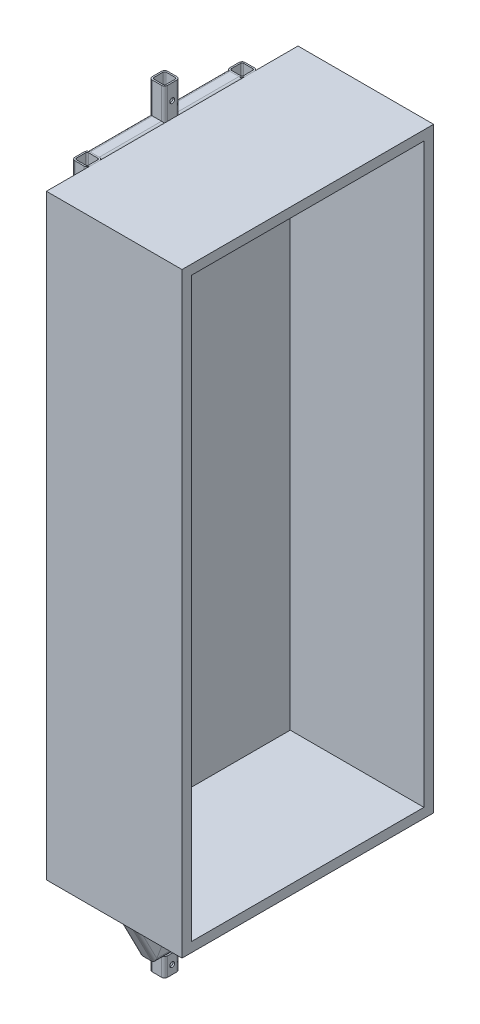
SolidWorks part; units mm, degrees
ref_plane "Front Plane" through (0, 0, 0) normal (1, 0, 0) x (0, 1, 0)
ref_plane "Top Plane" through (0, 0, 0) normal (0, 0, 1) x (0, 1, 0)
ref_plane "Right Plane" through (0, 0, 0) normal (0, 1, 0) x (-1, 0, 0)
sketch "Sketch1" plane through (0, 0, 0) normal (1, 0, 0) x (0, 1, 0)
  line L0 (-254, 254) -> (-254, -254) construction
  line L1 (-482.6, 254) -> (482.6, 254) construction
  line L2 (-482.6, 254) -> (-482.6, -254) construction
  line L3 (-482.6, -254) -> (482.6, -254) construction
  line L4 (482.6, 254) -> (482.6, -254) construction
  line L5 (-482.6, 254) -> (482.6, -254) construction
  line L6 (-482.6, -254) -> (482.6, 254) construction
  line L11 (-254, 133.6842) -> (254, -133.6842) construction
  line L13 (254, 254) -> (254, -254) construction
  point P0 (0, 0)
  point P6 (0, 0)
  dimension "D1" = 965.2
  dimension "D2" = 508
  dimension "D3" = 254
  dimension "D4" = 508
sketch3d "3DSketch1"
  line L0 (0, -381, 101.6) -> (0, -546.5837, 16.5565)
  line L7 (0, 0, 101.6) -> (0, 0, -101.6)
  line L8 (0, -381, 101.6) -> (0, 381, 101.6)
  line L9 (0, 381, 0) -> (0, 431.8, 0)
  line L11 (0, -381, 101.6) -> (0, -381, -101.6)
  line L12 (0, -381, -101.6) -> (0, 381, -101.6)
  line L13 (0, 381, 101.6) -> (0, 381, -101.6)
  line L14 (0, -381, 101.6) -> (0, 381, -101.6) construction
  line L15 (0, -381, -101.6) -> (0, 381, 101.6) construction
  line L16 (0, 254, 127) -> (0, 254, -127)
  line L17 (0, 254, 254) -> (0, 254, -254) construction
  line L18 (0, -546.5837, -16.4635) -> (0, -381, -101.6)
  line L19 (0, -546.5837, 16.5565) -> (0, -546.5837, -16.4635)
  line L20 (0, -581.0602, 0) -> (0, -546.5837, 0)
  point P0 (0, 0, 0)
  point P7 (0, 0, 0)
  point P8 (0, 0, 0)
  dimension "D1" = 50.8
  dimension "D3" = 101.6
  dimension "D2" = 762
  dimension "D4" = 25.4
  dimension "D5" = 25.4
  dimension "D6" = 33.02
ref_plane "Plane2" through (0, -381, 101.6) normal (0, 0, -1) x (1, 0, 0)
ref_plane "Plane4" through (0, -381, 101.6) normal (0, 1, 0) x (1, 0, 0)
ref_plane "Plane5" through (0, -381, 101.6) normal (0, 0, -1) x (1, 0, 0)
ref_plane "Plane6" through (0, -381, 101.6) normal (0, 0, -1) x (1, 0, 0)
ref_plane "Plane7" through (0, -381, -101.6) normal (0, 1, 0) x (1, 0, 0)
ref_plane "Plane8" through (0, -381, 101.6) normal (0, 0, -1) x (1, 0, 0)
ref_plane "Plane9" through (0, -381, 101.6) normal (0, 0, -1) x (1, 0, 0)
ref_plane "Plane10" through (0, -381, 101.6) normal (0, 0, -1) x (1, 0, 0)
ref_plane "Plane11" through (0, -381, -101.6) normal (0, 1, 0) x (1, 0, 0)
ref_plane "Plane12" through (0, -381, 101.6) normal (0, 0, -1) x (1, 0, 0)
other "Pipe 21.3 X 2.3(1)"
ref_plane "Plane15" through (0, 0, 101.6) normal (0, 0, -1) x (1, 0, 0)
sketch "Sketch136" plane through (0, 0, 101.6) normal (0, 0, -1) x (1, 0, 0)
  circle A0 centre (0, 0) radius 8.35
  circle A1 centre (0, 0) radius 10.65
  point P3 (0, 10.65)
  point P5 (-10.65, 0)
  point P6 (0, -10.65)
  point P7 (10.65, 0)
  point P8 (0, 0)
  dimension "In_dia" = 16.7
  dimension "Out_dia" = 21.3
other "Square tube 20 X 20 X 2(7)"
ref_plane "Plane17" through (0, -381, -101.6) normal (0, 1, 0) x (1, 0, 0)
sketch "Sketch141" plane through (0, -381, -101.6) normal (0, 1, 0) x (1, 0, 0)
  line L0 (-6, -8) -> (6, -8)
  line L1 (-8, -6) -> (-8, 6)
  line L2 (6, 8) -> (-6, 8)
  line L3 (8, 6) -> (8, -6)
  line L4 (-6, -10) -> (6, -10)
  line L5 (-10, -6) -> (-10, 6)
  line L6 (6, 10) -> (-6, 10)
  line L7 (10, 6) -> (10, -6)
  arc A0 (10, 6) -> (6, 10) centre (6, 6) ccw
  arc A1 (6, -10) -> (10, -6) centre (6, -6) ccw
  arc A2 (-10, -6) -> (-6, -10) centre (-6, -6) ccw
  arc A3 (-6, 10) -> (-10, 6) centre (-6, 6) ccw
  arc A4 (-6, 8) -> (-8, 6) centre (-6, 6) ccw
  arc A5 (8, 6) -> (6, 8) centre (6, 6) ccw
  arc A6 (6, -8) -> (8, -6) centre (6, -6) ccw
  arc A7 (-8, -6) -> (-6, -8) centre (-6, -6) ccw
  point P0 (-10, 0)
  point P1 (10, 0)
  point P2 (0, 10)
  point P3 (0, -10)
  point P4 (0, 0)
  point P5 (-10, -10)
  point P6 (10, -10)
  point P7 (10, 10)
  point P8 (-10, 10)
  point P33 (0, 0)
  dimension "D1" = 4
  dimension "Thickness" = 2
  dimension "V_leg" = 20
other "Square tube 20 X 20 X 2(11)"
ref_plane "Plane19" through (0, -381, 101.6) normal (0, -0.8895, -0.4569) x (1, 0, 0)
sketch "Sketch146" plane through (0, -381, 101.6) normal (0, -0.8895, -0.4569) x (1, 0, 0)
  line L0 (-6, -8) -> (6, -8)
  line L1 (-8, -6) -> (-8, 6)
  line L2 (6, 8) -> (-6, 8)
  line L3 (8, 6) -> (8, -6)
  line L4 (-6, -10) -> (6, -10)
  line L5 (-10, -6) -> (-10, 6)
  line L6 (6, 10) -> (-6, 10)
  line L7 (10, 6) -> (10, -6)
  arc A0 (10, 6) -> (6, 10) centre (6, 6) ccw
  arc A1 (6, -10) -> (10, -6) centre (6, -6) ccw
  arc A2 (-10, -6) -> (-6, -10) centre (-6, -6) ccw
  arc A3 (-6, 10) -> (-10, 6) centre (-6, 6) ccw
  arc A4 (-6, 8) -> (-8, 6) centre (-6, 6) ccw
  arc A5 (8, 6) -> (6, 8) centre (6, 6) ccw
  arc A6 (6, -8) -> (8, -6) centre (6, -6) ccw
  arc A7 (-8, -6) -> (-6, -8) centre (-6, -6) ccw
  point P0 (-10, 0)
  point P1 (10, 0)
  point P2 (0, 10)
  point P3 (0, -10)
  point P4 (0, 0)
  point P5 (-10, -10)
  point P6 (10, -10)
  point P7 (10, 10)
  point P8 (-10, 10)
  point P33 (0, 0)
  dimension "D1" = 4
  dimension "Thickness" = 2
  dimension "V_leg" = 20
sketch "Sketch147" plane through (10, 0, 0) normal (1, 0, 0) x (0, 1, 0)
  line L0 (-556.5837, -6) -> (-581.0602, -6) construction
  line L1 (-581.0602, 6) -> (-556.5837, 6) construction
  line L2 (-581.0602, 6) -> (-581.0602, -6) construction
  line L3 (-581.0602, -6) -> (-556.5837, -6) construction
  line L4 (-556.5837, 6) -> (-556.5837, -6) construction
  line L5 (-556.5837, -10) -> (-556.5837, -6) construction
  line L6 (-581.0602, 0) -> (-546.5837, 0) construction
  line L7 (391, -91.6) -> (391, 91.6) construction
  line L8 (431.8, 10) -> (391, 10) construction
  line L9 (431.8, 10) -> (431.8, -9.9139) construction
  line L10 (431.8, -9.9139) -> (391, -9.9139) construction
  line L11 (391, 10) -> (391, -9.9139) construction
  circle A0 centre (-569.6204, 0) radius 3.175
  circle A1 centre (411.4, 0) radius 3.175
  dimension "D1" = 6.35
  dimension "D2" = 6.35
sketch "Sketch148" plane through (0, 0, -127) normal (0, 0, -1) x (-1, 0, 0)
  circle A0 centre (0, 254) radius 8.35 construction
  circle A1 centre (0, 254) radius 8.35
extrude "Cut-Extrude3" cut sketch "Sketch148" against normal through all
sketch "Sketch154" plane through (-10, 0, 0) normal (-1, 0, 0) x (0, -1, 0)
  line L2 (-391, 111.6) -> (-391, -111.6)
  line L4 (391, 111.6) -> (391, -111.6)
  line L6 (-391, 111.6) -> (-391, 164.94)
  line L7 (-391, 164.94) -> (391, 164.94)
  line L8 (391, 111.6) -> (391, 164.94)
  line L10 (-391, -111.6) -> (-391, -164.94)
  line L11 (-391, -164.94) -> (391, -164.94)
  line L12 (391, -111.6) -> (391, -164.94)
  dimension "D1" = 53.34
  dimension "D2" = 53.34
extrude "Boss-Extrude2" add sketch "Sketch154" against normal blind 177.8 from surface at -20 separate body starting at face at (10, 0, 101.6)
sketch "Sketch156" plane through (187.8, 0, 0) normal (1, 0, 0) x (0, 1, 0)
  line L17 (378.3, -152.24) -> (378.3, 152.24)
  line L18 (-378.3, -152.24) -> (378.3, -152.24)
  line L19 (-378.3, 152.24) -> (-378.3, -152.24)
  line L20 (378.3, 152.24) -> (-378.3, 152.24)
  line L21 (378.3, -152.24) -> (378.3, 152.24)
  line L22 (-378.3, -152.24) -> (378.3, -152.24)
  line L23 (-378.3, 152.24) -> (-378.3, -152.24)
  line L24 (378.3, 152.24) -> (-378.3, 152.24)
  dimension "D1" = 12.7
extrude "Cut-Extrude6" cut sketch "Sketch156" against normal blind 175.26
extrude "Cut-Extrude8" cut sketch "Sketch147" against normal through all
